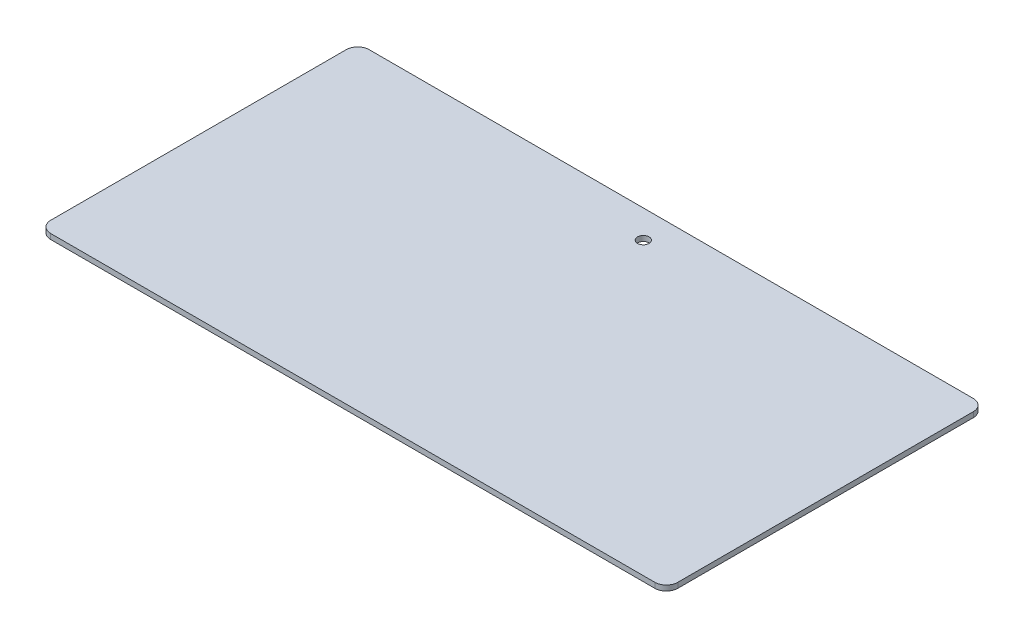
SolidWorks part; units mm, degrees
ref_plane "前视基准面" through (0, 0, 0) normal (0, 0, 1) x (1, 0, 0)
ref_plane "上视基准面" through (0, 0, 0) normal (0, 1, 0) x (1, 0, 0)
ref_plane "右视基准面" through (0, 0, 0) normal (1, 0, 0) x (0, 0, -1)
other "Configuration Table"
sketch "草图1" plane through (0, 0, 0) normal (0, 1, 0) x (1, 0, 0)
  line L0 (38.4414, 0) -> (38.4414, 97)
  line L1 (38.4414, 97) -> (229.4414, 97)
  line L2 (229.4414, 97) -> (229.4414, 0)
  line L3 (229.4414, 0) -> (38.4414, 0)
extrude "凸台-拉伸2" add sketch "草图1" along normal blind 1.6
fillet "圆角1" radius 3.5 4 edges at (38.4414, 0.8, -97) (38.4414, 0.8, 0) (229.4414, 0.8, -97) (229.4414, 0.8, 0)
sketch "草图3" plane through (0, 1.6, 0) normal (0, 1, 0) x (1, 0, 0)
  circle A0 centre (133.9414, 88.5) radius 1.75
extrude "切除-拉伸1" cut sketch "草图3" against normal through all
